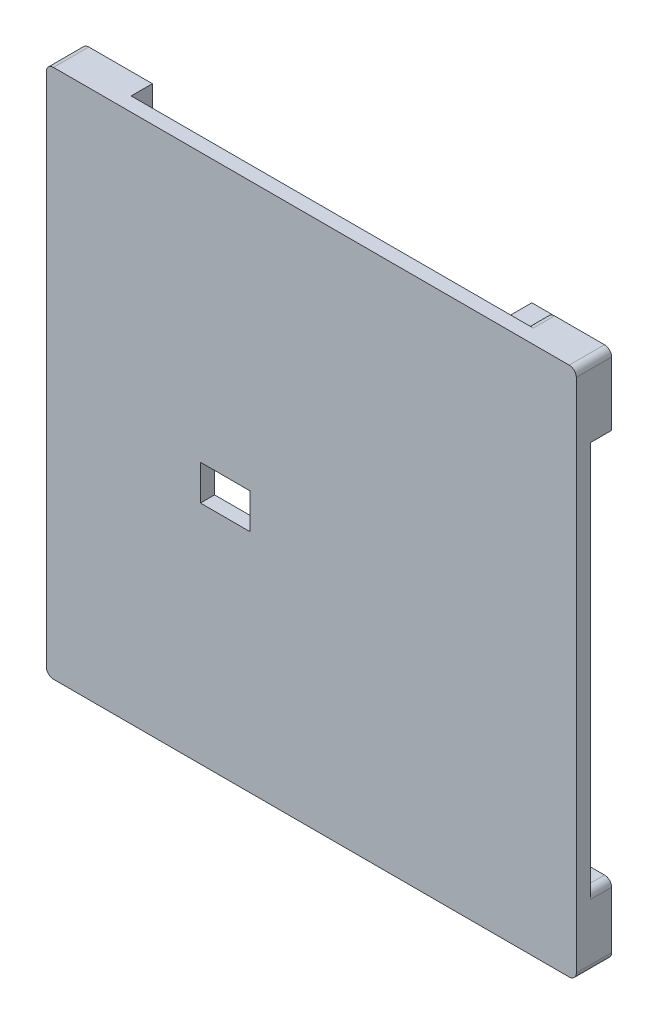
SolidWorks part; units mm, degrees
ref_plane "Plano frontal" through (0, 0, 0) normal (0, 0, 1) x (1, 0, 0)
ref_plane "Plano superior" through (0, 0, 0) normal (0, 1, 0) x (1, 0, 0)
ref_plane "Plano direito" through (0, 0, 0) normal (1, 0, 0) x (0, 0, -1)
sketch "Esboço1" plane through (0, 0, 0) normal (0, 0, 1) x (1, 0, 0)
  line L0 (75, -36.5) -> (75, -28.5) construction
  line L1 (74, -27.5) -> (66.909, -27.5) construction
  line L2 (65.909, -28.5) -> (65.909, -36.5) construction
  line L3 (66.909, -37.5) -> (74, -37.5) construction
  line L4 (65.909, 36.5) -> (65.909, 28.5) construction
  line L5 (66.909, 27.5) -> (75, 27.5) construction
  line L6 (10, -36.5) -> (10, -31.8)
  line L7 (9, -30.8) -> (8.409, -30.8)
  line L8 (8.409, -30.8) -> (8.409, -27.5)
  line L9 (8.409, -27.5) -> (0, -27.5)
  line L10 (0, -27.5) -> (0, -36.5)
  line L11 (1, -37.5) -> (9, -37.5)
  line L12 (10, -36.5) -> (10, -31.8)
  line L13 (9, -30.8) -> (8.409, -30.8)
  line L14 (8.409, -30.8) -> (8.409, -27.5)
  line L15 (8.409, -27.5) -> (0, -27.5)
  line L16 (0, -27.5) -> (0, -36.5)
  line L17 (1, -37.5) -> (9, -37.5)
  line L18 (75, 27.5) -> (75, 36.5) construction
  line L19 (74, 37.5) -> (66.909, 37.5) construction
  line L20 (75, -36.5) -> (75, -28.5)
  line L21 (74, -27.5) -> (66.909, -27.5)
  line L22 (65.909, -28.5) -> (65.909, -36.5)
  line L23 (66.909, -37.5) -> (74, -37.5)
  line L24 (65.909, 36.5) -> (65.909, 28.5)
  line L25 (66.909, 27.5) -> (75, 27.5)
  line L26 (75, 27.5) -> (75, 36.5)
  line L27 (74, 37.5) -> (66.909, 37.5)
  line L34 (9.9998, 31.8202) -> (9, 31.8202)
  line L35 (9, 37.5) -> (1, 37.5)
  line L36 (0, 36.5) -> (0, 28.5)
  line L37 (1, 27.5) -> (7.409, 27.5)
  line L38 (8.409, 28.5) -> (8.409, 30.8)
  line L39 (8.409, 30.8) -> (9, 30.8)
  line L41 (9, 37.5) -> (1, 37.5)
  line L42 (0, 36.5) -> (0, 28.5)
  line L43 (1, 27.5) -> (7.409, 27.5)
  line L44 (8.409, 28.5) -> (8.409, 30.8)
  line L45 (8.409, 30.8) -> (9, 30.8)
  line L169 (9, 31.8202) -> (9, 37.5)
  line L184 (9.9998, 31.8202) -> (9, 31.8202)
  line L198 (9, 31.8202) -> (9, 37.5)
  arc A0 (74, -37.5) -> (75, -36.5) centre (74, -36.5) ccw construction
  arc A1 (75, -28.5) -> (74, -27.5) centre (74, -28.5) ccw construction
  arc A2 (66.909, -27.5) -> (65.909, -28.5) centre (66.909, -28.5) ccw construction
  arc A3 (9, -37.5) -> (10, -36.5) centre (9, -36.5) ccw
  arc A4 (10, -31.8) -> (9, -30.8) centre (9, -31.8) ccw
  arc A5 (0, -36.5) -> (1, -37.5) centre (1, -36.5) ccw
  arc A6 (9, -37.5) -> (10, -36.5) centre (9, -36.5) ccw
  arc A7 (10, -31.8) -> (9, -30.8) centre (9, -31.8) ccw
  arc A8 (0, -36.5) -> (1, -37.5) centre (1, -36.5) ccw
  arc A10 (66.909, 37.5) -> (65.909, 36.5) centre (66.909, 36.5) ccw construction
  arc A11 (65.909, 28.5) -> (66.909, 27.5) centre (66.909, 28.5) ccw construction
  arc A12 (75, 36.5) -> (74, 37.5) centre (74, 36.5) ccw construction
  arc A13 (74, -37.5) -> (75, -36.5) centre (74, -36.5) ccw
  arc A14 (75, -28.5) -> (74, -27.5) centre (74, -28.5) ccw
  arc A15 (66.909, -27.5) -> (65.909, -28.5) centre (66.909, -28.5) ccw
  arc A16 (65.909, -36.5) -> (66.909, -37.5) centre (66.909, -36.5) ccw
  arc A17 (66.909, 37.5) -> (65.909, 36.5) centre (66.909, 36.5) ccw
  arc A18 (65.909, 28.5) -> (66.909, 27.5) centre (66.909, 28.5) ccw
  arc A19 (75, 36.5) -> (74, 37.5) centre (74, 36.5) ccw
  arc A25 (9, 30.8) -> (9.9998, 31.8202) centre (9, 31.8) ccw
  arc A27 (1, 37.5) -> (0, 36.5) centre (1, 36.5) ccw
  arc A28 (0, 28.5) -> (1, 27.5) centre (1, 28.5) ccw
  arc A29 (7.409, 27.5) -> (8.409, 28.5) centre (7.409, 28.5) ccw
  arc A30 (9, 30.8) -> (9.9998, 31.8202) centre (9, 31.8) ccw
  arc A32 (1, 37.5) -> (0, 36.5) centre (1, 36.5) ccw
  arc A33 (0, 28.5) -> (1, 27.5) centre (1, 28.5) ccw
  arc A34 (7.409, 27.5) -> (8.409, 28.5) centre (7.409, 28.5) ccw
  dimension "D1" = 0
  dimension "D2" = 0
extrude "Ressalto-extrusão1" add sketch "Esboço1" along normal blind 3
sketch "Esboço2" plane through (0, 0, 3) normal (0, 0, 1) x (1, 0, 0)
  line L0 (1, 37.5) -> (74, 37.5)
  line L1 (74, -37.5) -> (1, -37.5)
  line L4 (75, 36.5) -> (75, -36.5)
  line L5 (0, -36.5) -> (0, 36.5)
  arc A0 (74, -37.5) -> (75, -36.5) centre (74, -36.5) ccw construction
  arc A1 (74, -37.5) -> (75, -36.5) centre (74, -36.5) ccw
  arc A2 (75, 36.5) -> (74, 37.5) centre (74, 36.5) ccw construction
  arc A3 (1, 37.5) -> (0, 36.5) centre (1, 36.5) ccw construction
  arc A4 (1, 37.5) -> (0, 36.5) centre (1, 36.5) ccw
  arc A5 (0, -36.5) -> (1, -37.5) centre (1, -36.5) ccw construction
  arc A6 (0, -36.5) -> (1, -37.5) centre (1, -36.5) ccw
  arc A7 (75, 36.5) -> (74, 37.5) centre (74, 36.5) ccw
extrude "Ressalto-extrusão2" add sketch "Esboço2" along normal blind 2
ref_plane "Plano1" through (74, 37.5, 0) normal (-1, 0, 0) x (0, 0, 1)
sketch "Esboço13" plane through (0, 0, 3) normal (0, 0, -1) x (-1, 0, 0)
  line L0 (-9.9998, 31.8202) -> (-9.9998, 37.5)
  line L1 (-66.909, 37.5) -> (-9, 37.5) construction
  line L2 (-9.9998, 37.5) -> (-9, 37.5)
  line L3 (-9, 37.5) -> (-9, 31.8202)
  line L4 (-9, 31.8202) -> (-9.9998, 31.8202)
extrude "Ressalto-extrusão3" add sketch "Esboço13" along normal up to surface (3 mm away) up to face at (5.7485, 31.6658, 0)
sketch "Esboço20" plane through (0, 0, 0) normal (0, 0, -1) x (-1, 0, 0)
  line L0 (-8.409, 31.8) -> (-8.9998, 31.8)
  line L1 (-9.9998, 37.5) -> (-9.9998, 31.8202) construction
  line L2 (-9.9998, 32.8) -> (-9.9998, 30.8)
  line L3 (-9.9998, 30.8) -> (-8.409, 30.8)
  line L4 (-8.409, 31.8) -> (-8.409, 30.8)
  line L5 (0, 0) -> (-75, -0.5) construction
  line L6 (-75, -28.5) -> (-75, 27.5) construction
  line L7 (-8.409, -30.8) -> (-8.409, -31.8)
  line L8 (-8.409, -31.8) -> (-9, -31.8)
  line L9 (-10, -36.5) -> (-10, -31.8) construction
  line L10 (-8.409, -30.8) -> (-10, -30.8)
  line L11 (-10, -30.8) -> (-10, -32.8)
  arc A0 (-8.9998, 31.8) -> (-9.9998, 32.8) centre (-8.9998, 32.8) cw
  arc A1 (-9, -31.8) -> (-10, -32.8) centre (-9, -32.8) ccw
  dimension "D1" = 1
  dimension "D3" = 1
  dimension "D4" = 1
  dimension "D2" = 1
extrude "Corte-extrusão4" cut sketch "Esboço20" against normal up to surface (3 mm away) up to face at (33.2432, -0.323, 3)
sketch "Esboço22" plane through (0, 0, 3) normal (0, 0, -1) x (-1, 0, 0)
  line L0 (-8.409, 28.5) -> (-8.409, 31.8) construction
  line L1 (-11.609, 31.6) -> (-8.609, 31.6)
  line L2 (-11.609, 31.6) -> (-11.609, 29.5)
  line L3 (-11.609, 29.5) -> (-8.609, 29.5)
  line L4 (-8.609, 31.6) -> (-8.609, 29.5)
  line L5 (-8.409, 31.8) -> (-8.9998, 31.8) construction
  line L6 (-8.409, -31.8) -> (-8.409, -27.5) construction
  line L7 (-11.609, -29.5) -> (-8.609, -29.5)
  line L8 (-11.609, -29.5) -> (-11.609, -31.6)
  line L9 (-11.609, -31.6) -> (-8.609, -31.6)
  line L10 (-8.609, -29.5) -> (-8.609, -31.6)
  line L11 (-65.909, 36.5) -> (-65.909, 28.5) construction
  line L12 (-65.709, 36.5) -> (-62.709, 36.5)
  line L13 (-65.709, 36.5) -> (-65.709, 28.5)
  line L14 (-65.709, 28.5) -> (-62.709, 28.5)
  line L15 (-62.709, 36.5) -> (-62.709, 28.5)
  line L16 (-65.909, -28.5) -> (-65.909, -36.5) construction
  line L17 (-65.709, -28.5) -> (-62.709, -28.5)
  line L18 (-65.709, -28.5) -> (-65.709, -36.5)
  line L19 (-65.709, -36.5) -> (-62.709, -36.5)
  line L20 (-62.709, -28.5) -> (-62.709, -36.5)
  dimension "D1" = 3
  dimension "D2" = 2.1
  dimension "D3" = 0.2
  dimension "D4" = 0.2
  dimension "D5" = 3
  dimension "D6" = 2.1
  dimension "D7" = 0.2
  dimension "D8" = 0.2
  dimension "D9" = 0.2
  dimension "D10" = 3
  dimension "D11" = 0.2
  dimension "D12" = 3
extrude "Ressalto-extrusão5" add sketch "Esboço22" along normal blind 4
sketch "Esboço15" plane through (0, 0, 0) normal (0, 0, -1) x (-1, 0, 0)
  line L0 (-7.5, -29.25) -> (-1, -29.25) construction
  line L1 (-1, -29.25) -> (-1, -35.75) construction
  line L2 (-1, -35.75) -> (-7.5, -35.75) construction
  line L3 (-7.5, -35.75) -> (-7.5, -29.25) construction
  line L4 (-66.959, 29) -> (-73.959, 29) construction
  line L5 (-73.959, 36) -> (-66.959, 36) construction
  line L6 (-66.959, 36) -> (-66.959, 29) construction
  line L7 (-73.959, 29) -> (-73.959, 36) construction
  line L8 (-73.959, -36) -> (-73.959, -29) construction
  line L9 (-66.959, -36) -> (-73.959, -36) construction
  line L10 (-66.959, -29) -> (-66.959, -36) construction
  line L11 (-73.959, -29) -> (-66.959, -29) construction
  line L12 (-7.5, 29.25) -> (-7.5, 35.75) construction
  line L13 (-7.5, 35.75) -> (-1, 35.75) construction
  line L14 (-1, 35.75) -> (-1, 29.25) construction
  line L15 (-1, 29.25) -> (-7.5, 29.25) construction
  line L16 (-7.5, -29.25) -> (-1, -29.25) construction
  line L17 (-1, -29.25) -> (-1, -35.75) construction
  line L18 (-1, -35.75) -> (-7.5, -35.75) construction
  line L19 (-7.5, -35.75) -> (-7.5, -29.25) construction
  line L20 (-66.959, 29) -> (-73.959, 29) construction
  line L21 (-73.959, 36) -> (-66.959, 36) construction
  line L22 (-66.959, 36) -> (-66.959, 29) construction
  line L23 (-73.959, 29) -> (-73.959, 36) construction
  line L24 (-73.959, -36) -> (-73.959, -29) construction
  line L25 (-66.959, -36) -> (-73.959, -36) construction
  line L26 (-66.959, -29) -> (-66.959, -36) construction
  line L27 (-73.959, -29) -> (-66.959, -29) construction
  line L28 (-7.5, 29.25) -> (-7.5, 35.75) construction
  line L29 (-7.5, 35.75) -> (-1, 35.75) construction
  line L30 (-1, 35.75) -> (-1, 29.25) construction
  line L31 (-1, 29.25) -> (-7.5, 29.25) construction
  line L32 (-6, -30.75) -> (-2.5, -30.75)
  line L33 (-2.5, -30.75) -> (-2.5, -34.25)
  line L34 (-2.5, -34.25) -> (-6, -34.25)
  line L35 (-6, -34.25) -> (-6, -30.75)
  line L44 (-6, 30.75) -> (-6, 34.25)
  line L45 (-6, 34.25) -> (-2.5, 34.25)
  line L46 (-2.5, 34.25) -> (-2.5, 30.75)
  line L47 (-2.5, 30.75) -> (-6, 30.75)
  line L48 (-68.709, 30.75) -> (-72.209, 30.75)
  line L49 (-72.209, 30.75) -> (-72.209, 34.25)
  line L50 (-72.209, 34.25) -> (-68.709, 34.25)
  line L51 (-68.709, 34.25) -> (-68.709, 30.75)
  line L52 (-72.209, -34.25) -> (-72.209, -30.75)
  line L53 (-72.209, -30.75) -> (-68.709, -30.75)
  line L54 (-68.709, -30.75) -> (-68.709, -34.25)
  line L55 (-68.709, -34.25) -> (-72.209, -34.25)
  dimension "D1" = 1.5
  dimension "D2" = 1.75
extrude "Corte-extrusão1" cut sketch "Esboço15" against normal blind 3.5
sketch "Esboço16" plane through (0, 0, 3) normal (0, 0, -1) x (-1, 0, 0)
  line L0 (-22.7237, 3.8505) -> (-22.7237, 4.4905) construction
  line L1 (-27.8037, 1.3105) -> (-27.8037, 1.9505) construction
  line L2 (-22.7237, 3.8505) -> (-22.7237, 4.4905) construction
  line L3 (-27.8037, 1.3105) -> (-27.8037, 1.9505) construction
  line L4 (-27.8037, 1.3105) -> (-22.7237, 4.4905) construction
  line L6 (-29.2637, 6.9005) -> (-21.2637, 6.9005)
  line L7 (-29.2637, 6.9005) -> (-29.2637, -1.0995)
  line L8 (-29.2637, -1.0995) -> (-21.2637, -1.0995)
  line L9 (-21.2637, 6.9005) -> (-21.2637, -1.0995)
  line L10 (-29.2637, 6.9005) -> (-21.2637, -1.0995) construction
  line L11 (-29.2637, -1.0995) -> (-21.2637, 6.9005) construction
  point P4 (-25.2637, 2.9005)
  dimension "D1" = 8
  dimension "D2" = 8
extrude "Corte-extrusão2" cut sketch "Esboço16" against normal blind 1
sketch "Esboço18" plane through (0, 0, 3) normal (0, 0, -1) x (-1, 0, 0)
  line L1 (-21.8, -5.5) -> (-28.8, -5.5)
  line L2 (-21.8, -5.5) -> (-21.8, -0.5)
  line L3 (-21.8, -0.5) -> (-28.8, -0.5)
  line L4 (-28.8, -5.5) -> (-28.8, -0.5)
  line L6 (-66.909, 37.5) -> (-9.9998, 37.5) construction
  line L7 (0, 28.5) -> (0, -27.5) construction
  dimension "D1" = 38
  dimension "D2" = 21.8
  dimension "D3" = 7
  dimension "D4" = 5
extrude "Corte-extrusão3" cut sketch "Esboço18" against normal blind 10 contours L2 L3 L4 L1
